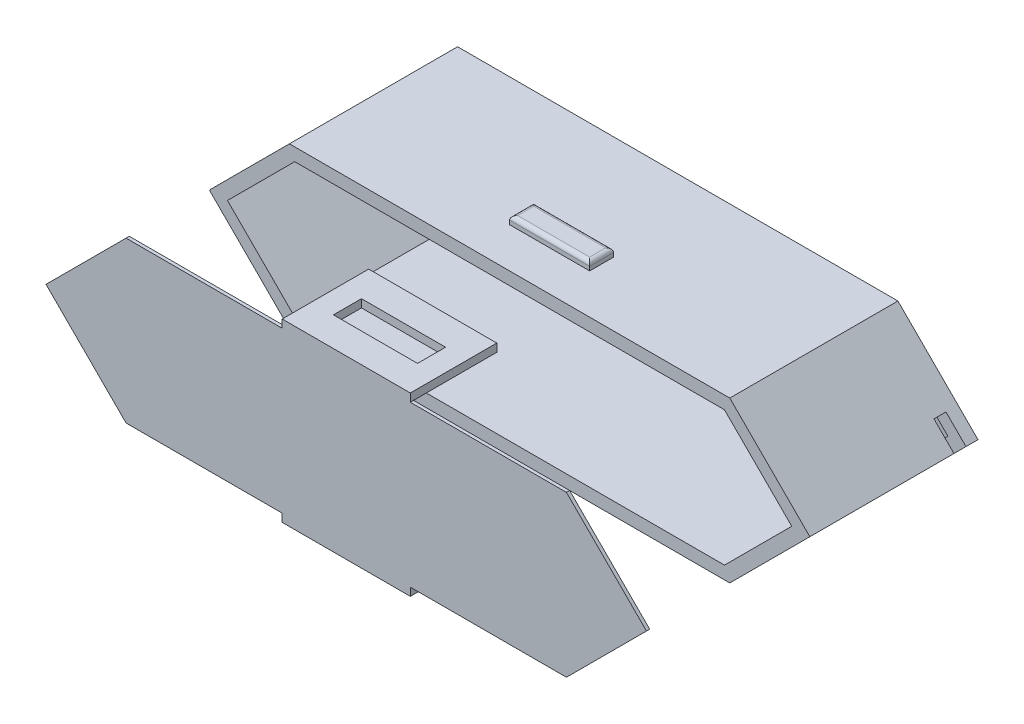
SolidWorks part; units mm, degrees
ref_plane "Plan de face" through (0, 0, 0) normal (0, 0, 1) x (1, 0, 0)
ref_plane "Plan de dessus" through (0, 0, 0) normal (0, 1, 0) x (1, 0, 0)
ref_plane "Plan de droite" through (0, 0, 0) normal (1, 0, 0) x (0, 0, -1)
sketch "Esquisse1" plane through (0, 0, 0) normal (0, 0, 1) x (1, 0, 0)
  line L5 (34.8454, 9.2514) -> (-20.1546, 9.2514)
  line L11 (-20.1546, 9.2514) -> (-30.1546, -0.7486)
  line L12 (-20.1546, 9.2514) -> (-20.1546, -0.7486) construction
  line L13 (-20.1546, -10.7486) -> (-30.1546, -0.7486)
  line L14 (7.3454, 9.2514) -> (7.3454, -0.7486) construction
  line L15 (-30.1546, -0.7486) -> (7.3454, -0.7486) construction
  line L16 (34.8454, -10.7486) -> (-20.1546, -10.7486)
  line L17 (34.8454, -10.7486) -> (44.8454, -0.7486)
  line L18 (34.8454, 9.2514) -> (44.8454, -0.7486)
  point P8 (7.3454, -10.7486)
  point P10 (0, 0)
  dimension "D1" = 37.5
  dimension "D2" = 27.5
  dimension "D3" = 10
extrude "Boss.-Extru.1" add sketch "Esquisse1" along normal blind 1
sketch "Esquisse2" plane through (0, 0, 1) normal (0, 0, 1) x (1, 0, 0)
  line L0 (-20.1546, -10.7486) -> (34.8454, -10.7486) construction
  line L1 (-30.1546, -0.7486) -> (-20.1546, -10.7486) construction
  line L2 (-20.1546, 9.2514) -> (-30.1546, -0.7486) construction
  line L3 (34.8454, -10.7486) -> (44.8454, -0.7486) construction
  line L4 (44.8454, -0.7486) -> (34.8454, 9.2514) construction
  line L5 (34.8454, 9.2514) -> (-20.1546, 9.2514) construction
  line L6 (-20.1546, -10.7486) -> (34.8454, -10.7486)
  line L7 (-30.1546, -0.7486) -> (-20.1546, -10.7486)
  line L8 (-20.1546, 9.2514) -> (-30.1546, -0.7486)
  line L9 (34.8454, -10.7486) -> (44.8454, -0.7486)
  line L10 (44.8454, -0.7486) -> (34.8454, 9.2514)
  line L11 (34.8454, 9.2514) -> (-20.1546, 9.2514)
  line L12 (-19.4919, 7.6514) -> (-27.8919, -0.7486)
  line L13 (-27.8919, -0.7486) -> (-19.4919, -9.1486)
  line L14 (-19.4919, -9.1486) -> (34.1826, -9.1486)
  line L15 (34.1826, -9.1486) -> (42.5826, -0.7486)
  line L16 (42.5826, -0.7486) -> (34.1826, 7.6514)
  line L17 (34.1826, 7.6514) -> (-19.4919, 7.6514)
  dimension "D1" = 1.6
extrude "Boss.-Extru.2" add sketch "Esquisse2" along normal blind 20
sketch "Esquisse5" plane through (0, 0, 0) normal (1, 0, 0) x (0, 0, -1)
  line L0 (-21, -0.7486) -> (0, -0.7486) construction
  line L1 (-3, -3.2486) -> (-1.5, -3.2486)
  line L2 (-3, -3.2486) -> (-3, 1.7514)
  line L3 (-3, 1.7514) -> (-1.5, 1.7514)
  line L4 (-1.5, -3.2486) -> (-1.5, 1.7514)
  line L5 (-3, -3.2486) -> (-1.5, 1.7514) construction
  line L6 (-3, 1.7514) -> (-1.5, -3.2486) construction
  line L7 (0, 9.2514) -> (0, -0.7486) construction
  point P0 (-2.25, -0.7486)
  dimension "D1" = 5
  dimension "D2" = 1.5
  dimension "D3" = 1.5
extrude "Enlèv. mat.-Extru.1" cut sketch "Esquisse5" against normal through all both and the other way through all
sketch "Esquisse9" plane through (0, 9.2514, 0) normal (0, 1, 0) x (1, 0, 0)
  line L0 (7.3454, -21) -> (7.3454, 0) construction
  line L1 (34.8454, -21) -> (-20.1546, -21) construction
  line L2 (34.8454, 0) -> (-20.1546, 0) construction
  line L4 (12.3454, -16) -> (2.3454, -16)
  line L5 (12.3454, -16) -> (12.3454, -13)
  line L6 (12.3454, -13) -> (2.3454, -13)
  line L7 (2.3454, -16) -> (2.3454, -13)
  line L8 (12.3454, -16) -> (2.3454, -13) construction
  line L9 (12.3454, -13) -> (2.3454, -16) construction
  point P6 (7.3454, -14.5)
  dimension "D1" = 10
  dimension "D2" = 3
  dimension "D3" = 5
extrude "Boss.-Extru.5" add sketch "Esquisse9" along normal blind 1
fillet "Congé1" radius 0.5 4 edges at (12.3454, 10.2514, 14.5) (7.3454, 10.2514, 13) (2.3454, 10.2514, 14.5) (7.3454, 10.2514, 16)
sketch "Esquisse10" plane through (0, -10.7486, 0) normal (0, -1, 0) x (1, 0, 0)
  line L0 (7.3454, 21) -> (7.3454, 0) construction
  line L1 (-20.1546, 21) -> (34.8454, 21) construction
  line L2 (-20.1546, 0) -> (34.8454, 0) construction
  line L4 (12.3454, 13) -> (2.3454, 13)
  line L5 (12.3454, 13) -> (12.3454, 16)
  line L6 (12.3454, 16) -> (2.3454, 16)
  line L7 (2.3454, 13) -> (2.3454, 16)
  line L8 (12.3454, 13) -> (2.3454, 16) construction
  line L9 (12.3454, 16) -> (2.3454, 13) construction
  point P6 (7.3454, 14.5)
  dimension "D1" = 10
  dimension "D2" = 3
  dimension "D3" = 5
extrude "Boss.-Extru.6" add sketch "Esquisse10" along normal blind 1
fillet "Congé2" radius 0.5 4 edges at (2.3454, -11.7486, 14.5) (7.3454, -11.7486, 13) (12.3454, -11.7486, 14.5) (7.3454, -11.7486, 16)
ref_plane "Plan3" through (0, 0, 41) normal (0, 0, 1) x (1, 0, 0)
sketch "Esquisse12" plane through (0, 0, 41) normal (0, 0, 1) x (1, 0, 0)
  line L0 (44.8454, -0.7486) -> (34.8454, 9.2514) construction
  line L1 (34.8454, -10.7486) -> (44.8454, -0.7486) construction
  line L2 (-20.1546, -10.7486) -> (34.8454, -10.7486) construction
  line L3 (-30.1546, -0.7486) -> (-20.1546, -10.7486) construction
  line L4 (-20.1546, 9.2514) -> (-30.1546, -0.7486) construction
  line L5 (34.8454, 9.2514) -> (-20.1546, 9.2514) construction
  line L6 (44.8454, -0.7486) -> (34.8454, 9.2514)
  line L7 (34.8454, -10.7486) -> (44.8454, -0.7486)
  line L8 (-20.1546, -10.7486) -> (34.8454, -10.7486)
  line L9 (-30.1546, -0.7486) -> (-20.1546, -10.7486)
  line L10 (-20.1546, 9.2514) -> (-30.1546, -0.7486)
  line L11 (34.8454, 9.2514) -> (-20.1546, 9.2514)
extrude "Boss.-Extru.7" add sketch "Esquisse12" along normal blind 0.4 separate body
sketch "Esquisse13" plane through (0, 9.2514, 0) normal (0, 1, 0) x (1, 0, 0)
  line L0 (7.3454, -16) -> (7.3454, -41.4) construction
  line L1 (2.3454, -16) -> (12.3454, -16) construction
  line L2 (34.8454, -41.4) -> (-20.1546, -41.4) construction
  line L8 (15.3454, -30.6) -> (-0.6546, -30.6)
  line L9 (-11, -41) -> (11, -41) construction
  line L10 (12.5954, -37.75) -> (2.0954, -37.75)
  line L11 (1.5456, -36) -> (13.1451, -36) construction
  line L12 (12.5954, -37.75) -> (12.5954, -34.25)
  line L13 (12.5954, -34.25) -> (2.0954, -34.25)
  line L14 (2.0954, -37.75) -> (2.0954, -34.25)
  line L15 (12.5954, -37.75) -> (2.0954, -34.25) construction
  line L16 (12.5954, -34.25) -> (2.0954, -37.75) construction
  line L17 (15.3454, -30.6) -> (15.3454, -41.4)
  line L18 (15.3454, -41.4) -> (-0.6546, -41.4)
  line L19 (-0.6546, -30.6) -> (-0.6546, -41.4)
  line L20 (15.3454, -30.6) -> (-0.6546, -41.4) construction
  line L21 (15.3454, -41.4) -> (-0.6546, -30.6) construction
  point P9 (7.3454, -36)
  point P14 (7.3454, -36)
  dimension "D1" = 10.5
  dimension "D2" = 5
  dimension "D3" = 3.5
  dimension "D4" = 16
extrude "Boss.-Extru.8" add sketch "Esquisse13" along normal blind 1
ref_plane "Plan4" through (0, -0.7486, 0) normal (0, 1, 0) x (1, 0, 0)
mirror "Symétrie1" about plane through (0, -0.7486, 0) normal (0, 1, 0) of "Boss.-Extru.8"
